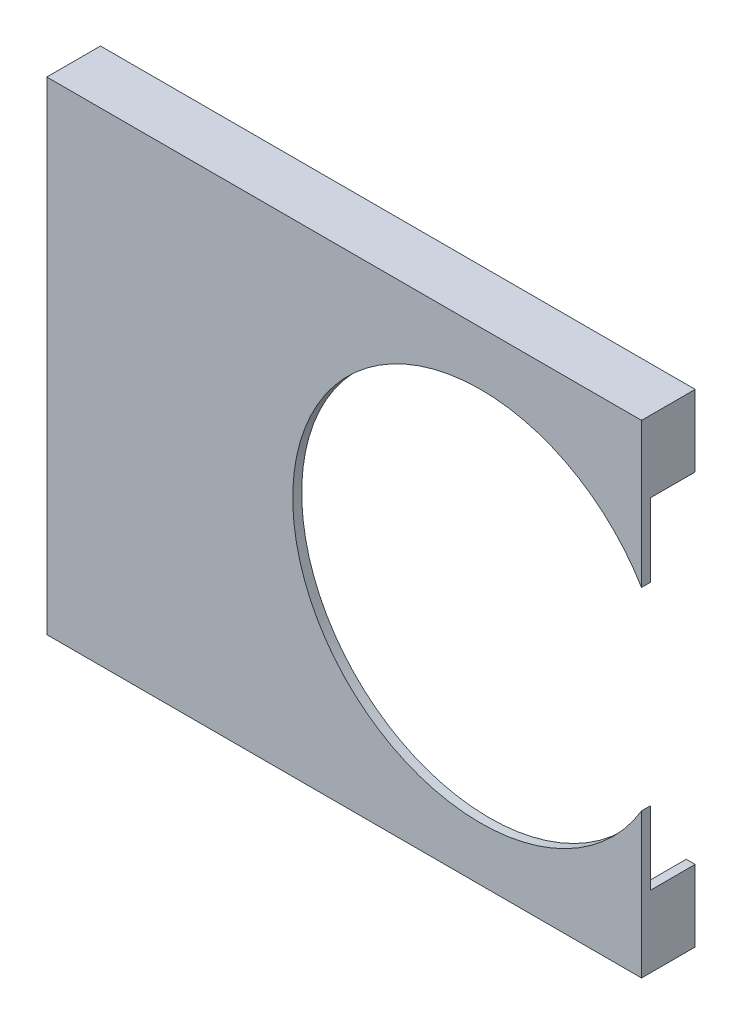
SolidWorks part; units mm, degrees
ref_plane "Front Plane" through (0, 0, 0) normal (0, 0, 1) x (1, 0, 0)
ref_plane "Top Plane" through (0, 0, 0) normal (0, 1, 0) x (1, 0, 0)
ref_plane "Right Plane" through (0, 0, 0) normal (1, 0, 0) x (0, 0, -1)
sketch "Sketch1" plane through (0, 0, 0) normal (0, 0, 1) x (1, 0, 0)
  line L1 (-33.25, 27) -> (33.25, 27)
  line L2 (-33.25, 27) -> (-33.25, -27)
  line L3 (-33.25, -27) -> (33.25, -27)
  line L4 (33.25, 27) -> (33.25, -27)
  circle A0 centre (15.25, 0) radius 21
  point P7 (33.25, 0)
  dimension "D1" = 42
  dimension "D2" = 54
  dimension "D3" = 18
  dimension "D4" = 66.5
extrude "Boss-Extrude1" add sketch "Sketch1" along normal blind 1 contours A0 L4 L1 L2 L3
sketch "Sketch2" plane through (0, 0, 1) normal (0, 0, 1) x (1, 0, 0)
  line L0 (33.25, -10.8167) -> (33.25, -27) construction
  line L1 (-33.25, -27) -> (33.25, -27)
  line L2 (-33.25, -27) -> (-33.25, -26)
  line L3 (-33.25, -26) -> (33.25, -26)
  line L4 (33.25, -27) -> (33.25, -26)
  line L5 (-33.25, 27) -> (-33.25, -27) construction
  line L6 (33.25, 27) -> (-33.25, 27)
  line L7 (33.25, 27) -> (33.25, 26)
  line L8 (33.25, 26) -> (-33.25, 26)
  line L9 (-33.25, 27) -> (-33.25, 26)
  line L10 (33.25, 27) -> (33.25, 10.8167) construction
  line L11 (32.25, -26) -> (33.25, -26)
  line L12 (32.25, -26) -> (32.25, -19)
  line L13 (32.25, -19) -> (33.25, -19)
  line L14 (33.25, -26) -> (33.25, -19)
  line L15 (33.25, 19) -> (32.25, 19)
  line L16 (33.25, 19) -> (33.25, 26)
  line L17 (33.25, 26) -> (32.25, 26)
  line L18 (32.25, 19) -> (32.25, 26)
  line L20 (-32.25, -26) -> (-33.25, -26)
  line L21 (-32.25, -26) -> (-32.25, -19)
  line L22 (-32.25, -19) -> (-33.25, -19)
  line L23 (-33.25, -26) -> (-33.25, -19)
  line L24 (-33.25, 19) -> (-32.25, 19)
  line L25 (-33.25, 19) -> (-33.25, 26)
  line L26 (-33.25, 26) -> (-32.25, 26)
  line L27 (-32.25, 19) -> (-32.25, 26)
  dimension "D1" = 1
  dimension "D2" = 1
  dimension "D3" = 7
  dimension "D4" = 1
  dimension "D5" = 7
  dimension "D6" = 1
  dimension "D7" = 7
  dimension "D8" = 7
  dimension "D9" = 1
  dimension "D10" = 1
extrude "Boss-Extrude2" add sketch "Sketch2" against normal blind 5 from surface at -1 contours L24 L27 L8 L0 | L21 L22 L0 L3 | L16 L15 L18 L17 | L11 L12 L13 L14 starting at face at (4.5833, 0, 0)
